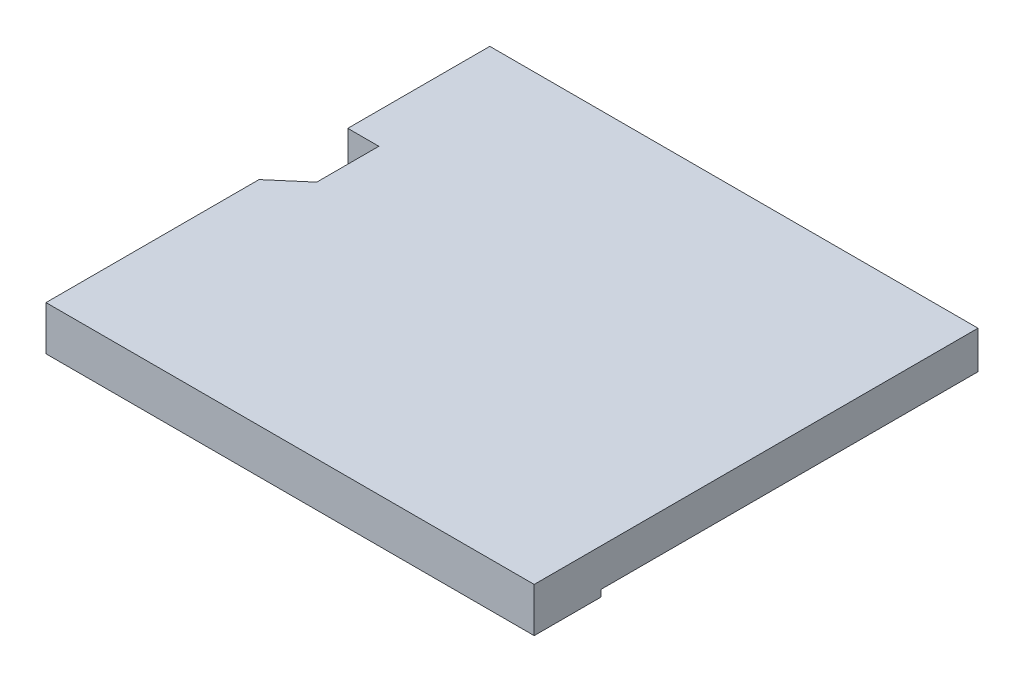
SolidWorks part; units mm, degrees
ref_plane "Front Plane" through (0, 0, 0) normal (0, 0, 1) x (1, 0, 0)
ref_plane "Top Plane" through (0, 0, 0) normal (0, 1, 0) x (1, 0, 0)
ref_plane "Right Plane" through (0, 0, 0) normal (1, 0, 0) x (0, 0, -1)
sketch "Sketch1" plane through (0, 0, 0) normal (0, 0, 1) x (1, 0, 0)
  line L0 (4.925, -3.3244) -> (4.925, -2.3144) construction
  line L1 (-4.925, -2.3144) -> (4.925, -2.3144)
  line L2 (-4.925, -2.3144) -> (-4.925, -3.1644)
  line L3 (-4.925, -3.1644) -> (4.925, -3.1644)
  line L4 (4.925, -2.3144) -> (4.925, -3.1644)
  line L5 (4.975, -3.1644) -> (4.825, -3.1644) construction
extrude "Boss-Extrude1" add sketch "Sketch1" along normal blind 10
sketch "Sketch2" plane through (0, -3.1644, 0) normal (0, -1, 0) x (1, 0, 0)
  line L0 (4.925, 10) -> (-4.925, 10) construction
  line L1 (4.925, 10) -> (-4.925, 10)
  arc A0 (0.34, -33.9739) -> (0.34, 2.0261) centre (0.34, -15.9739) ccw construction
  arc A1 (0.34, -33.9739) -> (-14.0672, -5.1835) centre (0.34, -15.9739) ccw
  point P3 (-14.0672, -5.1835)
  dimension "D1" = 7.9739
sketch "Sketch3" plane through (0, -3.1644, 0) normal (0, -1, 0) x (1, 0, 0)
  line L0 (4.925, 10) -> (-6.075, 10)
  line L1 (-6.075, 10) -> (-6.075, 5.2)
  line L2 (-6.075, 5.2) -> (-5.375, 4.6)
  line L3 (-5.375, 4.6) -> (-5.375, 3.2)
  line L4 (-5.375, 3.2) -> (-6.075, 3.2)
  line L5 (-6.075, 3.2) -> (-6.075, 0)
  line L6 (-6.075, 0) -> (-4.925, 0)
  line L7 (-4.925, 0) -> (-4.925, 10)
  line L8 (4.925, 10) -> (4.925, 0) construction
  line M12 (-4.925, 10) -> (-4.925, 0)
  dimension "D1" = 11
  dimension "D2" = 10.3
  dimension "D3" = 4.8
  dimension "D4" = 2
  dimension "D5" = 1.4
extrude "Boss-Extrude2" add sketch "Sketch3" against normal up to surface (0.85 mm away) contours L5 L6 L0 L1 L2 L3 L4 M12 up to face at (0, -2.3144, 5)
sketch "Sketch4" plane through (0, -3.1644, 0) normal (0, -1, 0) x (1, 0, 0)
  line L0 (-6.075, 10) -> (4.925, 10) construction
  line L1 (-6.075, 10) -> (4.925, 10)
  line L2 (-6.075, 10) -> (-6.075, 8.5)
  line L3 (-6.075, 10) -> (-6.075, 5.2) construction
  line L4 (-6.075, 8.5) -> (4.925, 8.5) construction
  line L5 (4.925, 10) -> (4.925, 0) construction
  line L6 (4.925, 8.5) -> (4.925, 10)
  arc A0 (-6.075, 8.5) -> (4.925, 8.5) centre (-0.575, 68.875) ccw
  dimension "D1" = 1.5
  dimension "D2" = 1.75
extrude "Boss-Extrude3" add sketch "Sketch4" along normal offset from surface (0.15 mm away) 1 up to face at (-3.15, -2.3144, 4.525)
